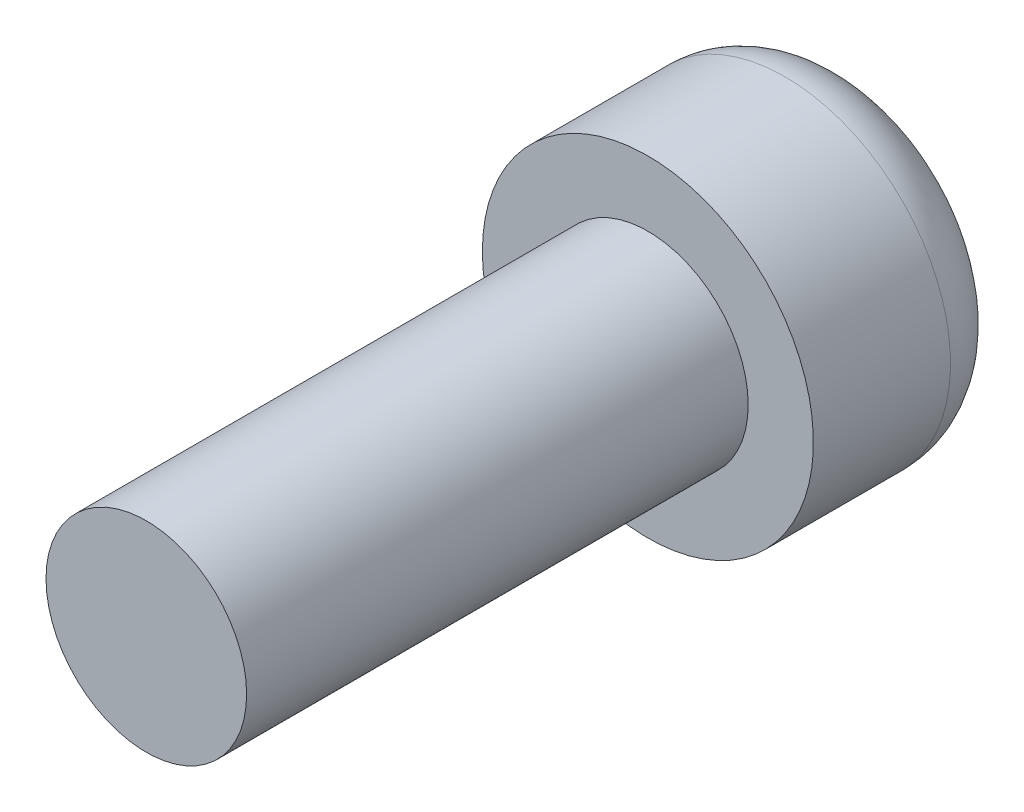
SolidWorks part; units mm, degrees
ref_plane "前视基准面" through (0, 0, 0) normal (0, 0, 1) x (1, 0, 0)
ref_plane "上视基准面" through (0, 0, 0) normal (0, 1, 0) x (1, 0, 0)
ref_plane "右视基准面" through (0, 0, 0) normal (1, 0, 0) x (0, 0, -1)
sketch "草图1" plane through (0, 0, 0) normal (0, 0, 1) x (1, 0, 0)
  circle A0 centre (0, 0) radius 3
extrude "凸台-拉伸1" add sketch "草图1" along normal blind 15
sketch "草图2" plane through (0, 0, 0) normal (0, 0, -1) x (-1, 0, 0)
  circle A0 centre (0, 0) radius 4.95
extrude "凸台-拉伸2" add sketch "草图2" along normal blind 6.1
fillet "圆角1" radius 2 1 edges at (-4.95, 0, -6.1)
